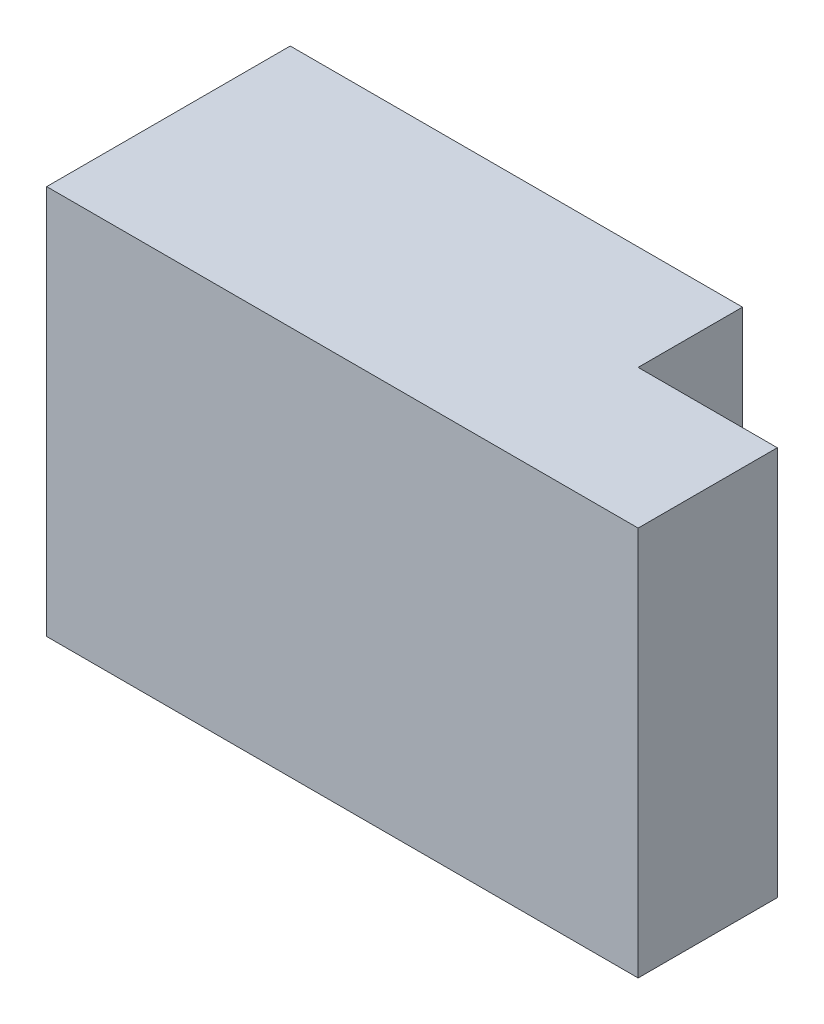
SolidWorks part; units mm, degrees
ref_plane "前视基准面" through (0, 0, 0) normal (0, 0, 1) x (1, 0, 0)
ref_plane "上视基准面" through (0, 0, 0) normal (0, 1, 0) x (1, 0, 0)
ref_plane "右视基准面" through (0, 0, 0) normal (1, 0, 0) x (0, 0, -1)
other "Configuration Table"
sketch "草图1" plane through (0, 0, 0) normal (0, 0, 1) x (1, 0, 0)
  line L0 (0, 0) -> (8.5795, 0) construction
  line L1 (32.5, -28) -> (-32.5, -28)
  line L2 (32.5, -28) -> (32.5, 28)
  line L3 (32.5, 28) -> (-32.5, 28)
  line L4 (-32.5, -28) -> (-32.5, 28)
  line L5 (32.5, -28) -> (-32.5, 28) construction
  line L6 (32.5, 28) -> (-32.5, -28) construction
  line L7 (0, 7.8062) -> (0, 0) construction
  circle A0 centre (-29, 24.5) radius 1.35
  circle A2 centre (29, 24.5) radius 1.35
  circle A3 centre (-29, -24.5) radius 1.35
  circle A4 centre (29, -24.5) radius 1.35
  point P0 (0, 0)
  dimension "D3" = 2.7
  dimension "D4" = 3.5
  dimension "D5" = 3.5
  dimension "D1" = 65
  dimension "D2" = 56
extrude "凸台-拉伸1" add sketch "草图1" along normal blind 15
sketch "草图2" plane through (0, 0, 15) normal (0, 0, 1) x (1, 0, 0)
  line L1 (-32.5, 28) -> (52.5, 28)
  line L2 (-32.5, 28) -> (-32.5, -28)
  line L3 (-32.5, -28) -> (52.5, -28)
  line L4 (52.5, 28) -> (52.5, -28)
  dimension "D1" = 56
  dimension "D2" = 85
extrude "凸台-拉伸2" add sketch "草图2" along normal blind 20
